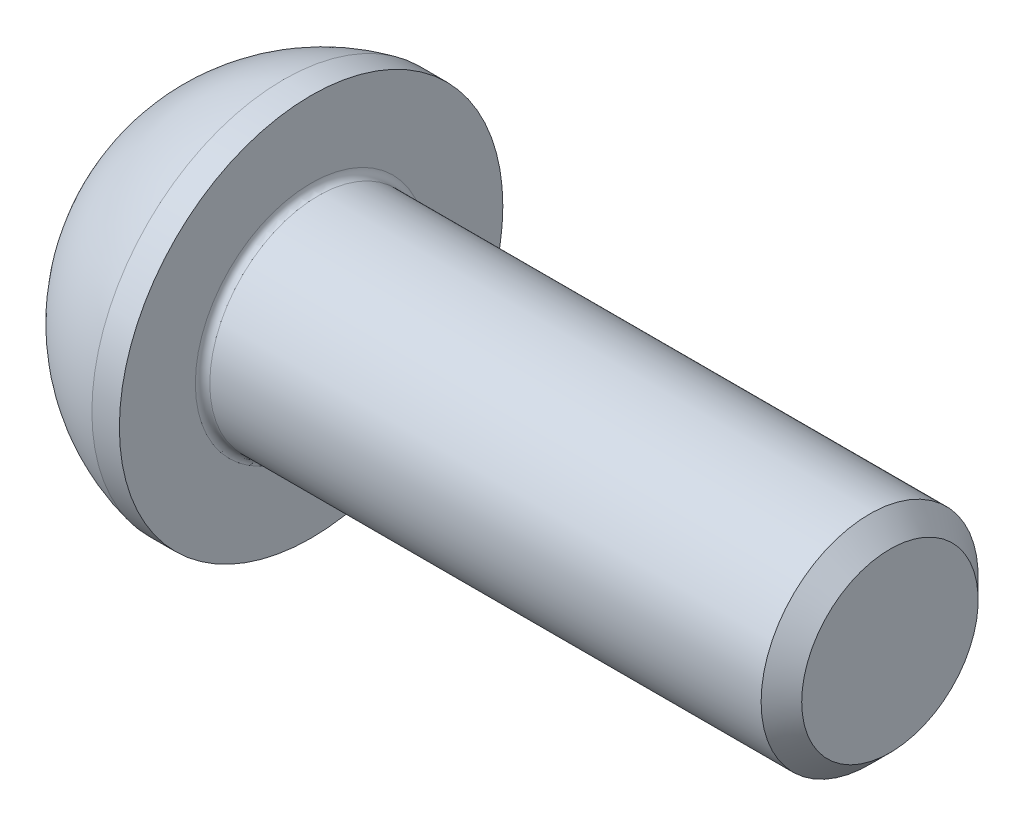
SolidWorks part; units mm, degrees
ref_plane "Plane1" through (0, 0, 0) normal (0, 0, 1) x (1, 0, 0)
ref_plane "Plane2" through (0, 0, 0) normal (0, 1, 0) x (1, 0, 0)
ref_plane "Plane3" through (0, 0, 0) normal (1, 0, 0) x (0, 0, -1)
sketch "BodySke" plane through (0, 0, 0) normal (0, 0, 1) x (1, 0, 0)
  line L0 (10.2, 0) -> (10.2, 1.2195)
  line L1 (9.9195, 1.5) -> (2.2, 1.5)
  line L2 (2.2, 1.5) -> (2.2, 2.65)
  line L3 (2.2, 2.65) -> (1.82, 2.65)
  line L4 (0, 0) -> (101.6, 0) construction
  line L5 (2.2, -2.65) -> (1.82, -2.65) construction
  line L6 (55.6768, -1.5) -> (2.2, -1.5) construction
  line L7 (10.2, 0) -> (0, 0)
  line L8 (0, 1.325) -> (0, -1.325) construction
  line L9 (0, 0) -> (0, 1.325)
  line L10 (10.2, 1.2195) -> (9.9195, 1.5)
  line L11 (10.2, -1.2195) -> (9.9195, -1.5) construction
  line L12 (2.7, 9.525) -> (2.7, -1.5) construction
  line L13 (2.2, 9.525) -> (2.2, -1.5) construction
  arc A1 (0, 1.325) -> (1.82, 2.65) centre (2.3569, 0) cw
  dimension "D1" = 2.65
  dimension "Diameter" = 3
  dimension "Length" = 8
  dimension "Head_dia" = 5.3
  dimension "Head_ht" = 2.2
  dimension "Head_side_ht" = 0.38
  dimension "Minor_dia" = 2.439
  dimension "Body_ch_ang" = 45
  dimension "Advance" = 0.5
  dimension "Thread_nom" = 8
revolve "BaseBody" add sketch "BodySke" angle 360 about L4
cosmetic thread "ThreadCosmetic" parameters "Thread_length"=7, "Thread_minor"=2.439
fillet "Fillet1" radius 0.1 1 edges at (2.2, 0, 1.5)
sketch "Sketch2" plane through (0, 0, 0) normal (0, 0, 1) x (1, 0, 0)
  line L0 (0, 1) -> (1.04, 1)
  line L1 (1.04, 1) -> (1.6174, 0)
  line L3 (1.6174, 0) -> (0, 0)
  line L4 (0, 0) -> (0, 1)
  line L5 (0, -1) -> (1.04, -1) construction
  line L6 (0, 0) -> (47.625, 0) construction
  dimension "D2" = 60
  dimension "PreBroach_depth" = 1.04
  dimension "PreBroach_dia" = 2
revolve "PreBroach" cut sketch "Sketch2" angle 360 about L6
sketch "Sketch3" plane through (0, 0, 0) normal (1, 0, 0) x (0, 0, -1)
  line L0 (-1, -0.5774) -> (-1, 0.5774)
  line L1 (-1, 0.5774) -> (0, 1.1547)
  line L2 (0, 1.1547) -> (1, 0.5774)
  line L3 (1, 0.5774) -> (1, -0.5774)
  line L4 (1, -0.5774) -> (0, -1.1547)
  line L5 (0, -1.1547) -> (-1, -0.5774)
  dimension "D1" = 1
  dimension "D2" = 1
  dimension "D3" = 2
  dimension "Hex_size" = 2
extrude "Hex" cut sketch "Sketch3" along normal blind 1.04
sketch "ThdSchSke" plane through (0, 0, 0) normal (0, 0, 1) x (1, 0, 0)
  line L0 (3.2, -1.2195) -> (3.0036, -1.5)
  line L1 (3.2, -1.2195) -> (3.3964, -1.5)
  line L2 (3.3964, -1.5) -> (3.3964, -1.875)
  line L3 (-3.175, 0) -> (5.1513, 0) construction
  line L5 (3.3964, -1.875) -> (3.0036, -1.875)
  line L6 (3.0036, -1.875) -> (3.0036, -1.5)
  dimension "Thread_minor" = 2.439
  dimension "Diameter" = 3
  dimension "Start" = 3.2
  dimension "SideAngle" = 55
  dimension "VeeAngle" = 70
  dimension "Overcut" = 3.75
revolve "ThreadSchematic" [suppressed] cut sketch "ThdSchSke" angle 360 about L3
pattern_linear "ThdSchPat" [suppressed]
equation "\"D1@BodySke\" = \"Head_dia@BodySke\" * .5"
equation "\"Thread_minor@ThreadCosmetic\" = \"Minor_dia@BodySke\""
equation "\"D1@Sketch3\" = \"Hex_size@Sketch3\" / 2"
equation "\"D2@Sketch3\" = \"D1@Sketch3\""
equation "\"D3@Sketch3\" = \"Hex_size@Sketch3\""
equation "\"Thread_length@ThreadCosmetic\" = ((sgn( (\"Length@BodySke\" - \"Advance@BodySke\" * 2.0) - \"Thread_nom@BodySke\" )-1)*( (\"Length@BodySke\" - \"Advance@BodySke\" * 2.0) - \"Thread_nom@BodySke\" ))/-2+ \"Thread_nom@BodySke\""
equation "\"Thread_minor@ThdSchSke\" = \"Minor_dia@BodySke\""
equation "\"Diameter@ThdSchSke\" = \"Diameter@BodySke\""
equation "\"Overcut@ThdSchSke\" = \"Diameter@BodySke\" * 1.25"
equation "\"Start@ThdSchSke\" = \"Head_ht@BodySke\" + \"Length@BodySke\" - \"Thread_length@ThreadCosmetic\"  '---Non-countersunk---"
equation "\"Num_threads@ThdSchPat\" = int( \"Thread_length@ThreadCosmetic\" / \"Advance@BodySke\" + 0.999 )  + 1"
equation "\"Advance@ThdSchPat\" = \"Thread_length@ThreadCosmetic\" /  (\"Num_threads@ThdSchPat\" - 1) 'relax it"
equation "\"Num_threads@ThdSchPat\" = \"Num_threads@ThdSchPat\" - sgn( \"Num_threads@ThdSchPat\" - 1) '---chamfered tips only---"
